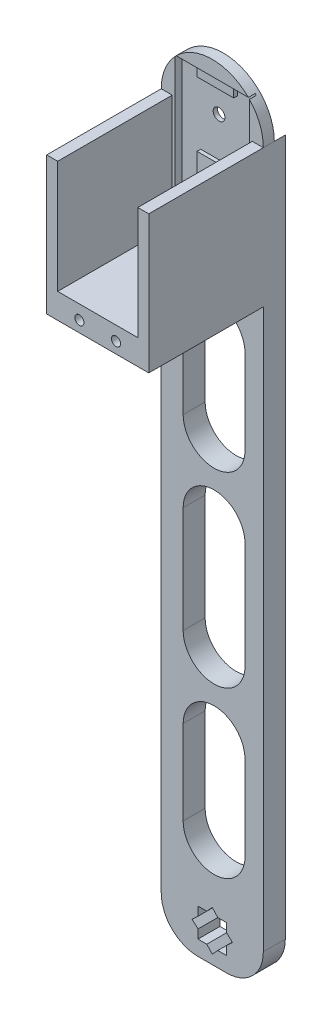
SolidWorks part; units mm, degrees
ref_plane "Plan de face" through (0, 0, 0) normal (0, 0, 1) x (1, 0, 0)
ref_plane "Plan de dessus" through (0, 0, 0) normal (0, 1, 0) x (1, 0, 0)
ref_plane "Plan de droite" through (0, 0, 0) normal (1, 0, 0) x (0, 0, -1)
sketch "Esquisse1" plane through (0, 0, 0) normal (0, 0, 1) x (1, 0, 0)
  line L1 (-9.8138, 31.7623) -> (18.0362, 31.7623)
  line L2 (-9.8138, 31.7623) -> (-9.8138, -168.2377)
  line L3 (-9.8138, -168.2377) -> (18.0362, -168.2377)
  line L4 (18.0362, 31.7623) -> (18.0362, -168.2377)
  arc A1 (18.0362, 31.7623) -> (-9.8138, 31.7623) centre (4.1112, 31.7623) ccw
  dimension "D1" = 27.85
  dimension "D2" = 200
extrude "Boss.-Extru.1" add sketch "Esquisse1" along normal blind 6 contours L4 L1 L2 L3 | L1 A1
sketch "Esquisse2" plane through (0, 0, 6) normal (0, 0, 1) x (1, 0, 0)
  line L0 (18.0362, 31.7623) -> (18.0362, -168.2377) construction
  line L1 (-5.6388, 41.5123) -> (13.8612, 41.5123)
  line L2 (-5.6388, 41.5123) -> (-5.6388, 1.0123)
  line L3 (-5.6388, 1.0123) -> (13.8612, 1.0123)
  line L4 (13.8612, 41.5123) -> (13.8612, 1.0123)
  line L5 (-9.8138, 31.7623) -> (-9.8138, -168.2377) construction
  line L6 (-5.6388, 1.0123) -> (13.8612, 1.0123)
  line L7 (-5.6388, 1.0123) -> (-5.6388, -5.9877)
  line L8 (-5.6388, -5.9877) -> (13.8612, -5.9877)
  line L9 (13.8612, 1.0123) -> (13.8612, -5.9877)
  line L10 (-5.6388, 1.0123) -> (-9.8138, 1.0123)
  line L11 (-5.6388, 1.0123) -> (-5.6388, -5.9877)
  line L12 (-5.6388, -5.9877) -> (-9.8138, -5.9877)
  line L13 (-9.8138, 1.0123) -> (-9.8138, -5.9877)
  line L15 (13.8612, -5.9877) -> (18.0362, -5.9877)
  line L16 (13.8612, -5.9877) -> (13.8612, 1.0123)
  line L17 (13.8612, 1.0123) -> (18.0362, 1.0123)
  line L18 (18.0362, -5.9877) -> (18.0362, 1.0123)
  line L19 (-9.8138, -5.9877) -> (18.0362, -5.9877)
  line L20 (-9.8138, -5.9877) -> (-9.8138, -8.9877)
  line L21 (-9.8138, -8.9877) -> (18.0362, -8.9877)
  line L22 (18.0362, -5.9877) -> (18.0362, -8.9877)
  circle A0 centre (4.1112, 31.7623) radius 2.925
  circle A1 centre (-0.9088, -1.9877) radius 1.5
  circle A2 centre (9.1312, -1.9877) radius 1.5
  line M5 (18.0362, -168.2377) -> (18.0362, 31.7623)
  line M7 (-9.8138, 31.7623) -> (-9.8138, -168.2377)
  dimension "D4" = 9.75
  dimension "D5" = 5.85
  dimension "D6" = 3
  dimension "D7" = 3
  dimension "D8" = 3
  dimension "D9" = 3
  dimension "D1" = 19.5
  dimension "D2" = 40.5
  dimension "D3" = 4.175
  dimension "D10" = 4.73
  dimension "D11" = 4.73
  dimension "D12" = 7
  dimension "D13" = 3
sketch "Esquisse4" plane through (0, 0, 6) normal (0, 0, 1) x (1, 0, 0)
  line L0 (18.0362, 31.7623) -> (18.0362, -168.2377) construction
  line L1 (-9.8138, -168.2377) -> (18.0362, -168.2377) construction
  line L2 (1.5131, -158.7377) -> (1.5131, -161.7377)
  line L3 (0.2157, -156.3423) -> (8.0067, -156.3423)
  line L4 (0.2157, -156.3423) -> (0.2157, -164.1332)
  line L5 (8.0067, -156.3423) -> (8.0067, -164.1332)
  line L6 (0.2157, -164.1332) -> (8.0067, -164.1332)
  line L7 (4.1112, -154.7287) -> (2.6157, -156.3423)
  line L8 (4.1112, -154.7287) -> (5.6067, -156.3423)
  line L9 (-1.3978, -160.2377) -> (0.2157, -158.7423)
  line L10 (-1.3978, -160.2377) -> (0.2157, -161.7332)
  line L11 (4.1112, -165.7468) -> (2.6157, -164.1332)
  line L12 (4.1112, -165.7468) -> (5.6067, -164.1332)
  line L13 (8.0067, -158.7423) -> (9.6202, -160.2377)
  line L14 (8.0067, -161.7332) -> (9.6202, -160.2377)
  circle A0 centre (4.1112, -160.2377) radius 3
  circle A2 centre (4.1112, -160.2377) radius 5.509
  dimension "D1" = 6
  dimension "D2" = 13.925
  dimension "D3" = 8
  dimension "D4" = 3
  dimension "D6" = 2.2
  dimension "D7" = 2.4
  dimension "D8" = 2.4
  dimension "D9" = 2.2
  dimension "D10" = 2.2
  dimension "D11" = 2.4
  dimension "D12" = 2.4
  dimension "D13" = 2.4
  dimension "D14" = 2.2
  dimension "D15" = 2.2
  dimension "D16" = 2.2
  dimension "D17" = 0
extrude "Enlèv. mat.-Extru.3" cut sketch "Esquisse4" against normal blind 29 contours L8 L7 L3 | L4 L6 L5 L3 A0 | L9 L10 L4 | L11 L12 L6 | L5 L14 L13 | L2 A0 | L2 A0
sketch "Esquisse5" plane through (0, 0, 0) normal (0, 0, -1) x (-1, 0, 0)
  circle A0 centre (-4.1112, 31.7623) radius 13.925
extrude "Enlèv. mat.-Extru.4" cut sketch "Esquisse5" against normal blind 3
sketch "Esquisse6" [suppressed] plane through (0, 0, 0) normal (0, 0, -1) x (-1, 0, 0)
  line L0 (-9.6613, 18.9911) -> (-18.0362, -0.2801)
  line L1 (-18.0362, 31.7623) -> (-18.0362, -168.2377) construction
  line L2 (-18.0362, -0.2801) -> (-18.0362, 31.7623)
  arc A0 (-18.0362, 31.7623) -> (9.8138, 31.7623) centre (-4.1112, 31.7623) ccw construction
  arc A1 (-18.0362, 31.7623) -> (9.8138, 31.7623) centre (-4.1112, 31.7623) ccw construction
  arc A2 (-18.0362, 31.7623) -> (-9.6613, 18.9911) centre (-4.1112, 31.7623) ccw
extrude "Enlèv. mat.-Extru.5" [suppressed] cut sketch "Esquisse6" against normal blind 3
sketch "Esquisse7" plane through (0, 0, 0) normal (0, 0, -1) x (-1, 0, 0)
  line L1 (-13.0362, -115.2377) -> (3.8338, -115.2377)
  line L2 (-13.0362, -115.2377) -> (-13.0362, -138.2377)
  line L3 (-13.0362, -138.2377) -> (3.8338, -138.2377)
  line L4 (3.8338, -115.2377) -> (3.8338, -138.2377)
  line L5 (-18.0362, 31.7623) -> (-18.0362, -168.2377) construction
  line L6 (9.8138, -168.2377) -> (-18.0362, -168.2377) construction
  line L8 (3.8338, -93.2377) -> (-13.0362, -93.2377)
  line L9 (3.8338, -93.2377) -> (3.8338, -64.2377)
  line L10 (3.8338, -64.2377) -> (-13.0362, -64.2377)
  line L11 (-13.0362, -93.2377) -> (-13.0362, -64.2377)
  line L12 (3.8338, -19.2377) -> (-13.0362, -19.2377)
  line L13 (3.8338, -19.2377) -> (3.8338, -42.2377)
  line L14 (3.8338, -42.2377) -> (-13.0362, -42.2377)
  line L15 (-13.0362, -19.2377) -> (-13.0362, -42.2377)
  arc A0 (-13.0362, -138.2377) -> (3.8338, -138.2377) centre (-4.6012, -138.2377) ccw
  arc A1 (-13.0362, -115.2377) -> (3.8338, -115.2377) centre (-4.6012, -115.2377) cw
  arc A2 (-13.0362, -93.2377) -> (3.8338, -93.2377) centre (-4.6012, -93.2377) ccw
  arc A3 (3.8338, -64.2377) -> (-13.0362, -64.2377) centre (-4.6012, -64.2377) ccw
  arc A4 (3.8338, -42.2377) -> (-13.0362, -42.2377) centre (-4.6012, -42.2377) cw
  arc A5 (3.8338, -19.2377) -> (-13.0362, -19.2377) centre (-4.6012, -19.2377) ccw
  dimension "D1" = 16.87
  dimension "D2" = 5
  dimension "D3" = 30
  dimension "D4" = 147
  dimension "D5" = 29
  dimension "D6" = 22
  dimension "D7" = 23
  dimension "D8" = 22
extrude "Enlèv. mat.-Extru.6" cut sketch "Esquisse7" against normal blind 13 contours A1 L1 | L4 L1 L2 L3 | L3 A0 | L8 A2 | L11 L8 L9 L10 | L10 A3 | A4 L14 | L12 L15 L14 L13 | L12 A5
fillet "Congé1" radius 10 1 edges at (18.0362, -168.2377, 3)
fillet "Congé2" radius 10 1 edges at (-9.8138, -168.2377, 3)
extrude "Boss.-Extru.2" [suppressed] add sketch "Esquisse2" along normal blind 30.75 contours L9 L3 L7 L8 A2 A1 | L12 L7 L10 M7 | L17 L9 L15 M5 | L21 L15 L8 L12 M7 M5
sketch "Esquisse8" plane through (0, 0, 3) normal (0, 0, -1) x (-1, 0, 0)
  circle A0 centre (-4.1112, 31.7623) radius 1.6
  dimension "D1" = 3.2
extrude "Enlèv. mat.-Extru.7" cut sketch "Esquisse8" against normal blind 10
sketch "Esquisse9" [suppressed] plane through (0, 0, 6) normal (0, 0, 1) x (1, 0, 0)
  line L0 (-9.8138, 1.0123) -> (18.0362, 1.0123) construction
  line L1 (-5.6538, 41.5923) -> (13.8462, 41.5923)
  line L2 (-5.6538, 41.5923) -> (-5.6538, 1.0123)
  line L3 (-5.6538, 1.0123) -> (13.8462, 1.0123)
  line L4 (13.8462, 41.5923) -> (13.8462, 1.0123)
  line L5 (-9.8138, 31.7623) -> (-9.8138, 1.0123) construction
  dimension "D1" = 19.5
  dimension "D2" = 40.58
  dimension "D3" = 4.16
extrude "Boss.-Extru.3" [suppressed] add sketch "Esquisse9" along normal blind 3.75
sketch "Esquisse10" [suppressed] plane through (0, 0, 6) normal (0, 0, 1) x (1, 0, 0)
  line L0 (-9.8138, 1.0123) -> (18.0362, 1.0123)
  line L1 (-9.8138, 1.0123) -> (-9.8138, 31.7623)
  line L6 (-9.8138, 1.0123) -> (18.0362, 1.0123) construction
  line L7 (18.0362, 31.7623) -> (18.0362, 1.0123) construction
  line L8 (18.0362, 1.0123) -> (18.0362, 31.7623)
  arc A0 (-9.8138, 31.7623) -> (18.0362, 31.7623) centre (4.1112, 31.7623) cw
extrude "Boss.-Extru.4" [suppressed] add sketch "Esquisse10" along normal blind 3.75
sketch "Esquisse11" plane through (0, 0, 6) normal (0, 0, 1) x (1, 0, 0)
  line L1 (-6.0388, 41.6123) -> (14.2612, 41.6123)
  line L2 (-6.0388, 41.6123) -> (-6.0388, 1.0123)
  line L3 (-6.0388, 1.0123) -> (14.2612, 1.0123)
  line L4 (14.2612, 41.6123) -> (14.2612, 1.0123)
  circle A0 centre (4.1112, 31.7623) radius 1.6 construction
  dimension "D3" = 9.85
  dimension "D1" = 20.3
  dimension "D2" = 40.6
  dimension "D4" = 10.15
extrude "Enlèv. mat.-Extru.8" cut sketch "Esquisse11" against normal blind 1.85
sketch "Esquisse12" plane through (0, 0, 6) normal (0, 0, 1) x (1, 0, 0)
  line L1 (-9.8138, 1.0123) -> (18.0362, 1.0123)
  line L2 (-9.8138, 1.0123) -> (18.0362, 1.0123)
  line L3 (18.0362, 1.0123) -> (-9.8138, 1.0123)
  line L4 (-9.8138, -5.8377) -> (18.0362, -5.8377)
  line L5 (-9.8138, 31.7623) -> (-9.8138, -158.2377) construction
  line L6 (-6.0388, 1.0123) -> (14.2612, 1.0123) construction
  line L7 (-9.8138, 1.0123) -> (-9.8138, -5.8377)
  line L8 (18.0362, 1.0123) -> (18.0362, -5.8377)
  line L15 (18.0362, 31.7623) -> (18.0362, -158.2377) construction
  dimension "D1" = 6.85
  dimension "D2" = 0
extrude "Boss.-Extru.5" add sketch "Esquisse12" along normal blind 31.25
sketch "Esquisse13" [suppressed] plane through (0, 0, 37.25) normal (0, 0, 1) x (1, 0, 0)
  line L1 (-9.8138, 1.0123) -> (-9.8138, -5.8377) construction
  line L3 (-0.8938, -2.8077) -> (9.1062, -2.8077) construction
  line L4 (18.0362, 1.0123) -> (-9.8138, 1.0123) construction
  circle A0 centre (-0.8938, -2.8077) radius 1.5
  circle A1 centre (9.1062, -2.8077) radius 1.5
  dimension "D1" = 10
  dimension "D5" = 3
  dimension "D3" = 3
  dimension "D2" = 3.82
  dimension "D4" = 8.92
extrude "Enlèv. mat.-Extru.9" [suppressed] cut sketch "Esquisse13" against normal blind 6
sketch "Esquisse14" plane through (0, 0, 4.15) normal (0, 0, 1) x (1, 0, 0)
  line L0 (-6.0388, 1.0123) -> (14.2612, 1.0123) construction
  line L1 (-0.8888, 21.0123) -> (9.1112, 21.0123)
  line L2 (-0.8888, 21.0123) -> (-0.8888, 1.0123)
  line L3 (-0.8888, 1.0123) -> (9.1112, 1.0123)
  line L4 (9.1112, 21.0123) -> (9.1112, 1.0123)
  line L5 (-6.0388, 41.2955) -> (-6.0388, 1.0123) construction
  line L7 (13.9541, 41.6123) -> (-5.7317, 41.6123) construction
  line L8 (-0.8888, 41.6123) -> (9.1112, 41.6123)
  line L9 (-0.8888, 41.6123) -> (-0.8888, 38.6123)
  line L10 (-0.8888, 38.6123) -> (9.1112, 38.6123)
  line L11 (9.1112, 41.6123) -> (9.1112, 38.6123)
  line L12 (-6.0388, 41.2955) -> (-6.0388, 1.0123) construction
  line L13 (14.2612, 1.0123) -> (14.2612, 41.2955) construction
  dimension "D1" = 10
  dimension "D2" = 5.15
  dimension "D3" = 20
  dimension "D4" = 5.15
  dimension "D5" = 5.15
  dimension "D6" = 3
extrude "Boss.-Extru.6" add sketch "Esquisse14" along normal blind 1
sketch "Esquisse15" plane through (0, 0, 6) normal (0, 0, 1) x (1, 0, 0)
  line L0 (-9.8138, 31.7623) -> (-9.8138, 1.0123) construction
  line L1 (18.0362, 31.7623) -> (18.0362, 1.0123) construction
  line L2 (-9.8138, 31.7623) -> (-9.8138, 1.0123)
  line L3 (18.0362, 31.7623) -> (18.0362, 1.0123)
  line L4 (-9.8138, 31.7623) -> (-6.8138, 31.7623)
  line L5 (-6.8138, 31.7623) -> (-6.8138, 1.0123)
  line L6 (-9.8138, 1.0123) -> (-6.0388, 1.0123) construction
  line L7 (-6.8138, 1.0123) -> (-9.8138, 1.0123)
  line L8 (18.0362, 31.7623) -> (15.0362, 31.7623)
  line L9 (15.0362, 31.7623) -> (15.0362, 1.0123)
  line L11 (15.0362, 1.0123) -> (18.0362, 1.0123)
  dimension "D1" = 3
  dimension "D2" = 3
extrude "Boss.-Extru.7" add sketch "Esquisse15" along normal blind 31.25
hole_wizard "Trou taraudé M31" [suppressed] positions "Esquisse17" profile "Esquisse16" tap size "M3" standard "ISO"
sketch "Esquisse17" [suppressed] plane through (0, 0, 37.25) normal (0, 0, 1) x (1, 0, 0)
  point P11 (-0.8938, -2.8077)
  point P14 (9.1062, -2.8077)
sketch "Esquisse16" plane through (-0.8938, -2.8077, 37.25) normal (1, 0, 0) x (0, -1, 0)
  line L0 (0, 0) -> (0, 9.2511)
  line L1 (0, 9.2511) -> (1.25, 8.5)
  line L2 (1.25, 8.5) -> (1.25, 0)
  line L5 (1.25, 0) -> (0, 0)
  line L10 (0, 9.2511) -> (-1.25, 8.5) construction
  line L11 (0, -6.35) -> (0, 107.95) construction
  dimension "Diamètre du trou pour taraudage" = 2.5
  dimension "Profondeur du trou pour taraudage" = 8.5
  dimension "Angle de pointe" = 118
cosmetic thread "Filetage de perçage1" parameters "D1"=6, "D2"=3
cosmetic thread "Filetage de perçage2" parameters "D1"=6, "D2"=3
hole_wizard "Trou taraudé M32" positions "Esquisse19" profile "Esquisse18" tap size "M3" standard "ISO"
sketch "Esquisse19" plane through (0, 0, 37.25) normal (0, 0, 1) x (1, 0, 0)
  line L0 (-9.8138, 31.7623) -> (-9.8138, -5.8377) construction
  line L1 (-6.0388, 1.0123) -> (-0.8888, 1.0123) construction
  line L2 (9.1112, 1.0123) -> (14.2612, 1.0123) construction
  point P0 (-0.8938, -2.8077)
  point P2 (9.1062, -2.8077)
  point P15 (42.5552, -8.581)
  dimension "D1" = 8.92
  dimension "D2" = 3.82
  dimension "D3" = 3.82
  dimension "D4" = 10
sketch "Esquisse18" plane through (-0.8938, -2.8077, 37.25) normal (1, 0, 0) x (0, -1, 0)
  line L0 (0, 0) -> (0, 9.2511)
  line L1 (0, 9.2511) -> (1.25, 8.5)
  line L2 (1.25, 8.5) -> (1.25, 0)
  line L5 (1.25, 0) -> (0, 0)
  line L10 (0, 9.2511) -> (-1.25, 8.5) construction
  line L11 (0, -6.35) -> (0, 107.95) construction
  dimension "Diamètre du trou pour taraudage" = 2.5
  dimension "Profondeur du trou pour taraudage" = 8.5
  dimension "Angle de pointe" = 118
cosmetic thread "Filetage de perçage3" parameters "D1"=6, "D2"=3
cosmetic thread "Filetage de perçage4" parameters "D1"=6, "D2"=3
